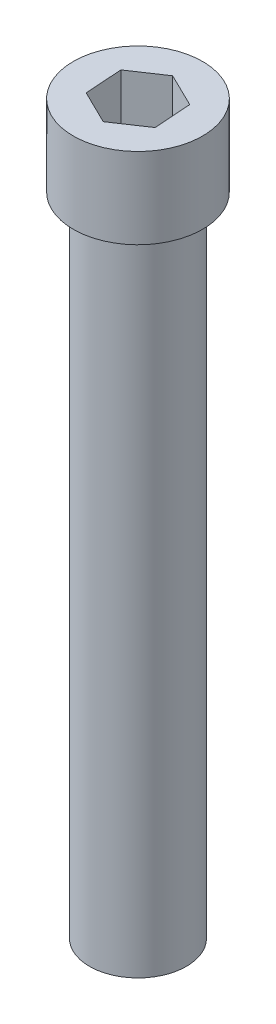
SolidWorks part; units mm, degrees
material "Plain Carbon Steel"
ref_plane "Front Plane" through (0, 0, 0) normal (0, 0, 1) x (1, 0, 0)
ref_plane "Top Plane" through (0, 0, 0) normal (0, 1, 0) x (1, 0, 0)
ref_plane "Right Plane" through (0, 0, 0) normal (1, 0, 0) x (0, 0, -1)
sketch "Sketch1" plane through (0, 0, 0) normal (0, 0, 1) x (1, 0, 0)
  line L0 (-4, 0) -> (-4, 5)
  line L1 (-4, 5) -> (0, 5)
  line L2 (0, 5) -> (0, -40)
  line L3 (0, -40) -> (-3, -40)
  line L4 (-3, -40) -> (-3, 0)
  line L5 (-3, 0) -> (-4, 0)
  dimension "D1" = 40
  dimension "D2" = 3
  dimension "D3" = 4
  dimension "D4" = 5
revolve "Revolve1" add sketch "Sketch1" angle 360 about L2
sketch "Sketch2" plane through (0, 5, 0) normal (0, 1, 0) x (1, 0, 0)
  line L1 (1.917, 1.2878) -> (-0.1568, 2.3041)
  line L2 (-0.1568, 2.3041) -> (-2.0738, 1.0162)
  line L3 (-2.0738, 1.0162) -> (-1.917, -1.2878)
  line L4 (-1.917, -1.2878) -> (0.1568, -2.3041)
  line L5 (0.1568, -2.3041) -> (2.0738, -1.0162)
  line L6 (2.0738, -1.0162) -> (1.917, 1.2878)
  circle A0 centre (0, 0) radius 2 construction
  dimension "D1" = 4
extrude "Cut-Extrude1" cut sketch "Sketch2" against normal blind 4
